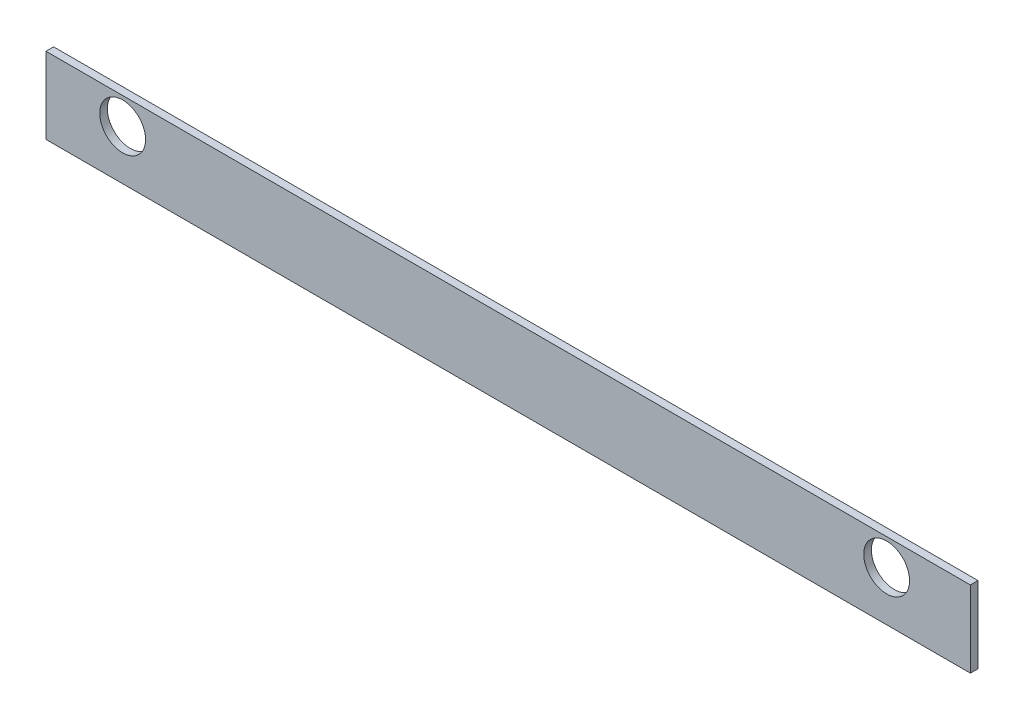
SolidWorks part; units mm, degrees
ref_plane "Front Plane" through (0, 0, 0) normal (0, 0, 1) x (1, 0, 0)
ref_plane "Top Plane" through (0, 0, 0) normal (0, 1, 0) x (1, 0, 0)
ref_plane "Right Plane" through (0, 0, 0) normal (1, 0, 0) x (0, 0, -1)
sketch "Sketch1" plane through (0, 0, 0) normal (0, 0, 1) x (1, 0, 0)
  line L0 (998.0436, -31.192) -> (0, -31.192) construction
  line L1 (-107.173, 3.808) -> (1102.7114, 3.808)
  line L2 (-107.173, 3.808) -> (-107.173, -96.192)
  line L3 (-107.173, -96.192) -> (1102.7114, -96.192)
  line L4 (1102.7114, 3.808) -> (1102.7114, -96.192)
  circle A1 centre (993.1696, -31.192) radius 30
  circle A2 centre (-6.8304, -31.192) radius 30
  point P11 (37.2351, -62.5218)
  point P12 (-6.8304, -48.192)
  dimension "D1" = 1000
  dimension "D3" = 60
  dimension "D4" = 35
  dimension "D5" = 100
extrude "Boss-Extrude1" add sketch "Sketch1" along normal blind 10
